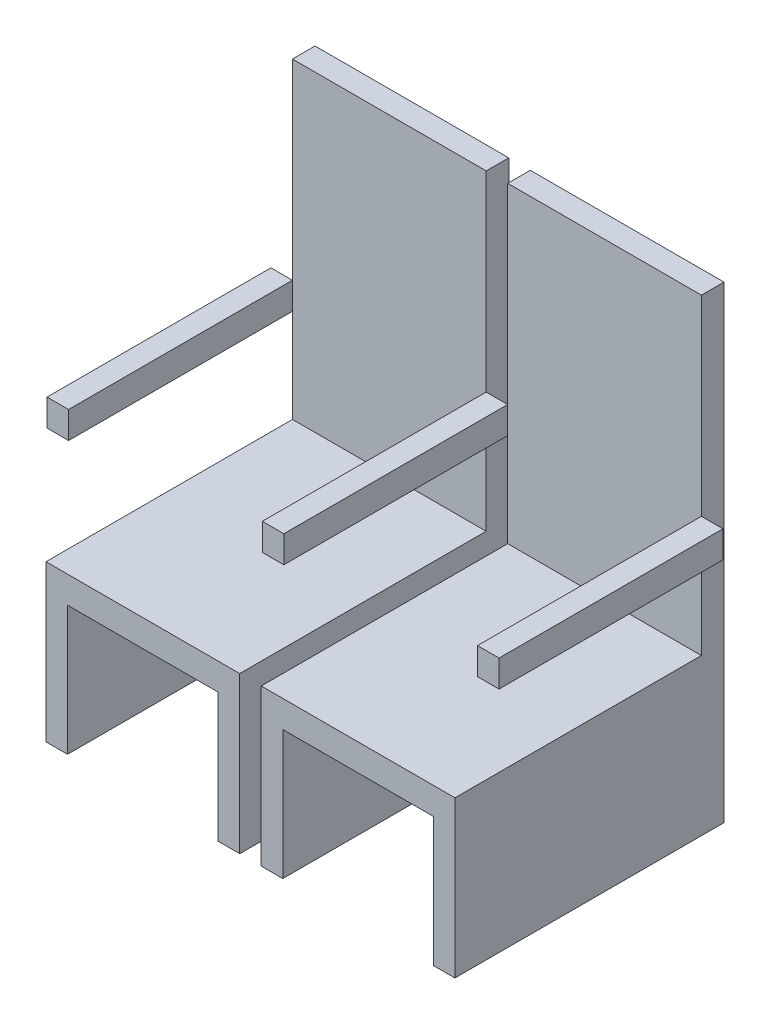
SolidWorks part; units mm, degrees
ref_plane "Front Plane" through (0, 0, 0) normal (0, 0, 1) x (1, 0, 0)
ref_plane "Top Plane" through (0, 0, 0) normal (0, 1, 0) x (1, 0, 0)
ref_plane "Right Plane" through (0, 0, 0) normal (1, 0, 0) x (0, 0, -1)
sketch "Sketch1" plane through (0, 0, 0) normal (0, 1, 0) x (1, 0, 0)
  line L0 (0, -40.079) -> (0, 40.079) construction
  line L13 (-533.4, 264.16) -> (-482.6, 264.16)
  line L14 (-482.6, 317.5) -> (-25.4, 317.5)
  line L15 (-533.4, 264.16) -> (-533.4, -264.16)
  line L16 (-482.6, -317.5) -> (-25.4, -317.5)
  line L17 (-25.4, 317.5) -> (-25.4, -317.5)
  line L18 (25.4, -317.5) -> (482.6, -317.5)
  line L19 (25.4, -317.5) -> (25.4, 317.5)
  line L20 (25.4, 317.5) -> (482.6, 317.5)
  line L21 (533.4, -264.16) -> (533.4, 264.16)
  line L22 (-482.6, 264.16) -> (-482.6, 317.5)
  line L23 (482.6, 264.16) -> (482.6, 317.5)
  line L24 (533.4, 264.16) -> (482.6, 264.16)
  line L25 (-34.7443, 0) -> (34.7443, 0) construction
  line L26 (482.6, -264.16) -> (482.6, -317.5)
  line L27 (-482.6, -264.16) -> (-482.6, -317.5)
  line L28 (-533.4, -264.16) -> (-482.6, -264.16)
  line L29 (533.4, -264.16) -> (482.6, -264.16)
  point P8 (-25.4, 0)
  point P9 (25.4, 0)
  dimension "D1" = 1066.8
  dimension "D2" = 50.8
  dimension "D3" = 50.8
  dimension "D4" = 53.34
  dimension "D5" = 635
  dimension "D6" = 25.4
extrude "Boss-Extrude1" add sketch "Sketch1" along normal blind 368.3
sketch "Sketch2" plane through (0, 368.3, 0) normal (0, 1, 0) x (1, 0, 0)
  line L0 (0, -202.565) -> (0, 202.565) construction
  line L1 (-482.6, 264.16) -> (-25.4, 264.16)
  line L2 (-482.6, 264.16) -> (-482.6, 317.5)
  line L3 (-482.6, 317.5) -> (-25.4, 317.5)
  line L4 (-25.4, 264.16) -> (-25.4, 317.5)
  line L5 (482.6, 317.5) -> (25.4, 317.5)
  line L6 (25.4, 264.16) -> (25.4, 317.5)
  line L7 (482.6, 264.16) -> (25.4, 264.16)
  line L8 (482.6, 264.16) -> (482.6, 317.5)
extrude "Boss-Extrude2" add sketch "Sketch2" along normal blind 736.6
sketch "Sketch3" plane through (0, 0, -264.16) normal (0, 0, 1) x (1, 0, 0)
  line L0 (-482.6, 1104.9) -> (-482.6, 368.3) construction
  line L1 (-482.6, 589.28) -> (-533.4, 589.28)
  line L2 (-482.6, 589.28) -> (-482.6, 652.78)
  line L3 (-482.6, 652.78) -> (-533.4, 652.78)
  line L4 (-533.4, 589.28) -> (-533.4, 652.78)
  line L5 (-533.4, 368.3) -> (-482.6, 368.3) construction
  line L6 (0, -349.25) -> (0, 349.25) construction
  line L7 (482.6, 652.78) -> (533.4, 652.78)
  line L8 (533.4, 589.28) -> (533.4, 652.78)
  line L9 (482.6, 589.28) -> (533.4, 589.28)
  line L10 (482.6, 589.28) -> (482.6, 652.78)
  line L11 (-25.4, 1104.9) -> (-25.4, 368.3) construction
  line L12 (-25.4, 589.28) -> (25.4, 589.28)
  line L13 (-25.4, 589.28) -> (-25.4, 652.78)
  line L14 (-25.4, 652.78) -> (25.4, 652.78)
  line L15 (25.4, 589.28) -> (25.4, 652.78)
  line L16 (25.4, 1104.9) -> (25.4, 368.3) construction
  dimension "D1" = 63.5
  dimension "D2" = 220.98
extrude "Boss-Extrude3" add sketch "Sketch3" along normal up to surface (528.32 mm away) separate body up to face at (-508, 184.15, 264.16)
sketch "Sketch4" plane through (0, 0, 317.5) normal (0, 0, 1) x (1, 0, 0)
  line L0 (-482.6, 0) -> (-25.4, 0) construction
  line L1 (-76.2, 0) -> (-431.8, 0)
  line L2 (-76.2, 0) -> (-76.2, 304.8)
  line L3 (-76.2, 304.8) -> (-431.8, 304.8)
  line L4 (-431.8, 0) -> (-431.8, 304.8)
  line L5 (-25.4, 368.3) -> (-25.4, 0) construction
  line L6 (-482.6, 368.3) -> (-482.6, 0) construction
  line L7 (-482.6, 368.3) -> (-25.4, 368.3) construction
  line L8 (0, -349.25) -> (0, 349.25) construction
  line L9 (-482.6, 0) -> (-533.4, 0)
  line L10 (-482.6, 0) -> (-482.6, 368.3)
  line L11 (-482.6, 368.3) -> (-533.4, 368.3)
  line L12 (-533.4, 0) -> (-533.4, 368.3)
  line L13 (76.2, 304.8) -> (431.8, 304.8)
  line L14 (431.8, 0) -> (431.8, 304.8)
  line L15 (76.2, 0) -> (431.8, 0)
  line L16 (76.2, 0) -> (76.2, 304.8)
  line L17 (482.6, 368.3) -> (533.4, 368.3)
  line L18 (533.4, 0) -> (533.4, 368.3)
  line L19 (482.6, 0) -> (533.4, 0)
  line L20 (482.6, 0) -> (482.6, 368.3)
  point P16 (0, 0)
  point P17 (0, 0)
  dimension "D1" = 50.8
  dimension "D2" = 50.8
  dimension "D3" = 63.5
extrude "Cut-Extrude1" cut sketch "Sketch4" against normal through all both and the other way through all
